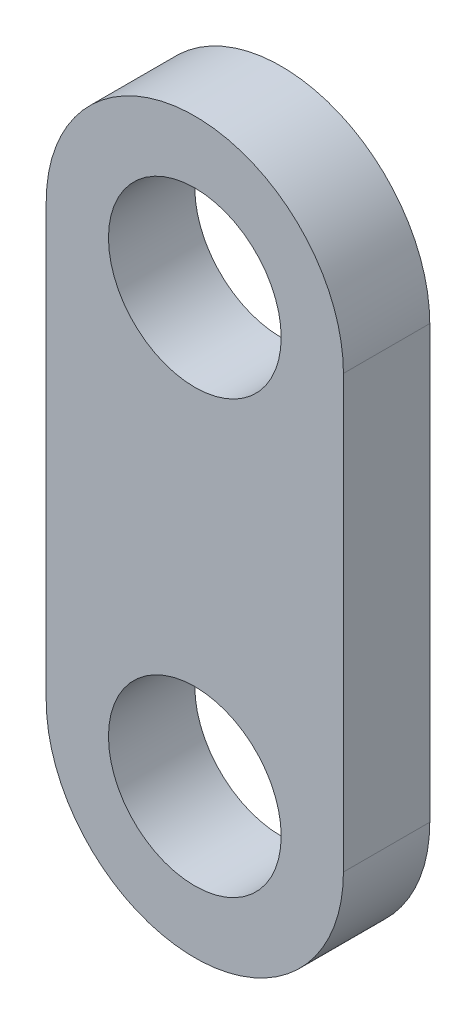
SolidWorks part; units mm, degrees
ref_plane "Alzado" through (0, 0, 0) normal (0, 0, 1) x (1, 0, 0)
ref_plane "Planta" through (0, 0, 0) normal (0, 1, 0) x (1, 0, 0)
ref_plane "Vista lateral" through (0, 0, 0) normal (1, 0, 0) x (0, 0, -1)
sketch "Croquis1" plane through (0, 0, 0) normal (0, 0, 1) x (1, 0, 0)
  line L0 (-0.4545, 6.2662) -> (-0.4545, -13.7338) construction
  line L1 (6.4286, 6.2662) -> (6.4286, -13.7338)
  line L2 (-7.3377, 6.2662) -> (-7.3377, -13.7338)
  arc A0 (6.4286, 6.2662) -> (-7.3377, 6.2662) centre (-0.4545, 6.2662) ccw
  arc A1 (-7.3377, -13.7338) -> (6.4286, -13.7338) centre (-0.4545, -13.7338) ccw
  circle A2 centre (-0.4545, 6.2662) radius 4
  circle A3 centre (-0.4545, -13.7338) radius 4
  point P2 (-0.4545, -3.7338)
  dimension "D2" = 8
  dimension "D3" = 8
  dimension "D1" = 20
extrude "Saliente-Extruir1" add sketch "Croquis1" along normal blind 4
